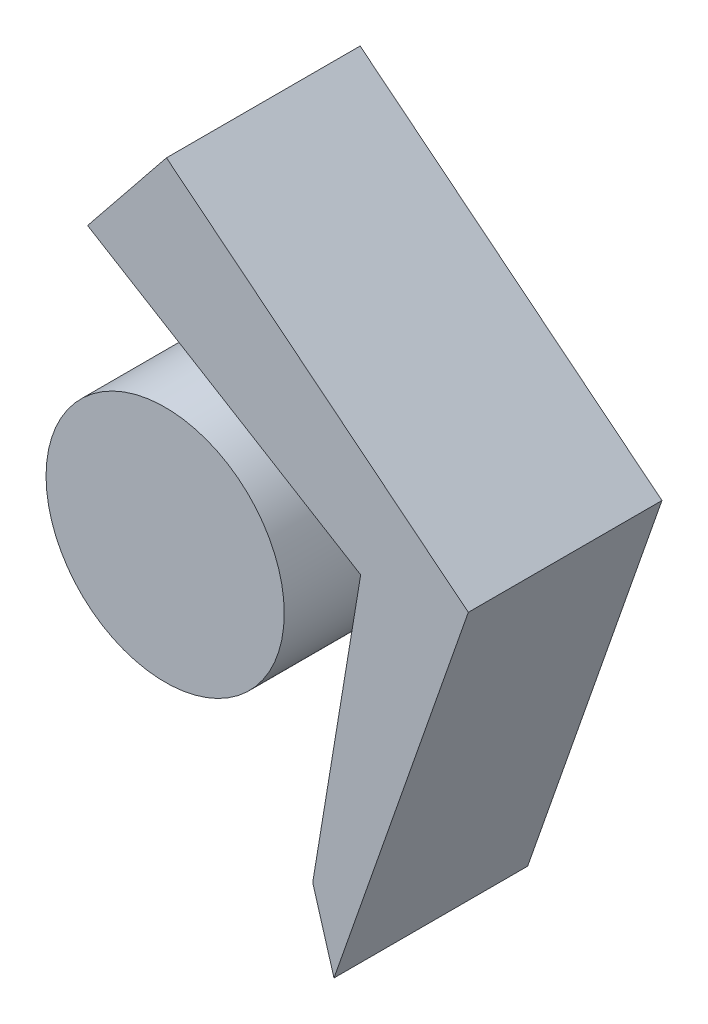
SolidWorks part; units mm, degrees
ref_plane "前视基准面" through (0, 0, 0) normal (0, 0, 1) x (1, 0, 0)
ref_plane "上视基准面" through (0, 0, 0) normal (0, 1, 0) x (1, 0, 0)
ref_plane "右视基准面" through (0, 0, 0) normal (1, 0, 0) x (0, 0, -1)
sketch "草图1" plane through (0, 0, 0) normal (0, 0, 1) x (1, 0, 0)
  line L6 (-118.1006, 243.6911) -> (193.6207, -6.9676)
  line L7 (193.6207, -6.9676) -> (54.8961, -403.396)
  line L8 (54.8961, -403.396) -> (32.9337, -328.9616)
  line L9 (32.9337, -328.9616) -> (82.4663, -28.9616)
  line L10 (82.4663, -28.9616) -> (-199.5647, 142.3817)
  line L11 (-199.5647, 142.3817) -> (-118.1006, 243.6911)
  circle A0 centre (-119.477, -103.0825) radius 123
  dimension "D1" = 400
  dimension "D2" = 420
  dimension "D3" = 330
  dimension "D4" = 130
  dimension "D5" = 300
extrude "凸台-拉伸1" add sketch "草图1" along normal blind 200
